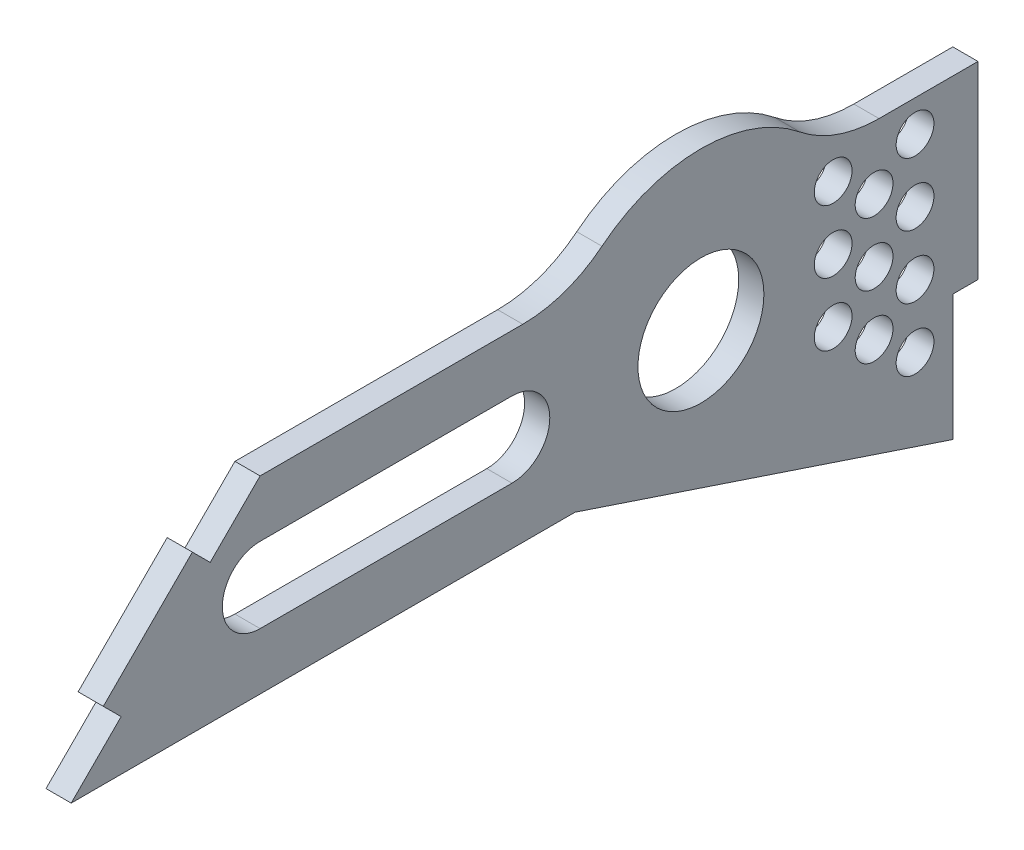
SolidWorks part; units mm, degrees
material "AISI 4340 Steel, normalized"
ref_plane "Front Plane" through (0, 0, 0) normal (0, 0, 1) x (1, 0, 0)
ref_plane "Top Plane" through (0, 0, 0) normal (0, 1, 0) x (1, 0, 0)
ref_plane "Right Plane" through (0, 0, 0) normal (1, 0, 0) x (0, 0, -1)
sketch "Sketch1" plane through (0, 0, 0) normal (1, 0, 0) x (0, 0, -1)
  line B0 (20, 0) -> (-20, 0)
  line B1 (-20, -12) -> (20, -12)
  line B2 (94, 49) -> (94, 24.7157)
  line B3 (21.7157, 9) -> (-20, 9)
  line B4 (-20, 9) -> (-50, -21)
  line B5 (-50, -21) -> (18.1966, -21)
  line B6 (40.5573, -26.2786) -> (90, -51)
  line B7 (90, -51) -> (90, 9)
  line B8 (90, 9) -> (94, 9)
  line B9 (94, 9) -> (94, -51)
  line B10 (94, -51) -> (119, 9)
  line B11 (119, 9) -> (119, 49)
  line B12 (119, 49) -> (94, 49)
  circle B13 centre (50, -6) radius 10
  arc B14 (20, -12) -> (20, 0) centre (20, -6) ccw
  arc B15 (78.2843, 9) -> (94, 24.7157) centre (78.2843, 24.7157) ccw
  arc B16 (65.7135, 13.4444) -> (78.2843, 9) centre (78.2843, 29) ccw
  arc B17 (65.7135, 13.4444) -> (34.2865, 13.4444) centre (50, -6) ccw
  arc B18 (21.7157, 9) -> (34.2865, 13.4444) centre (21.7157, 29) ccw
  arc B19 (40.5573, -26.2786) -> (18.1966, -21) centre (18.1966, -71) ccw
  arc B20 (-20, 0) -> (-20, -12) centre (-20, -6) ccw
  circle B21 centre (106.5, -6) radius 3
  circle B22 centre (106.5, 4) radius 3
  circle B23 centre (113, 9) radius 3
  circle B24 centre (106.5, 14) radius 3
  circle B25 centre (113, 19) radius 3
  circle B26 centre (106.5, 24) radius 3
  circle B27 centre (113, 29) radius 3
  circle B28 centre (113, 39) radius 3
  circle B29 centre (106.5, 34) radius 3
  circle B30 centre (100, 39) radius 3
  circle B31 centre (100, 29) radius 3
  circle B32 centre (100, 19) radius 3
  circle B33 centre (100, 9) radius 3
  circle B34 centre (100, -1) radius 3
  circle B35 centre (100, -11) radius 3
  circle B36 centre (100, -21) radius 3
  circle B37 centre (84, 4) radius 3
  circle B38 centre (84, -6) radius 3
  circle B39 centre (77.5, -1) radius 3
  circle B40 centre (71, 4) radius 3
  circle B41 centre (71, -6) radius 3
  circle B42 centre (77.5, -11) radius 3
  circle B43 centre (84, -16) radius 3
  circle B44 centre (71, -16) radius 3
  circle B45 centre (77.5, -21) radius 3
  circle B46 centre (84, -26) radius 3
  circle B47 centre (84, -36) radius 3
  circle B48 centre (77.5, -31) radius 3
  circle B49 centre (71, -26) radius 3
sketch_block_instance "Block-pedalbox side-1"
sketch_block "Block1"
sketch "Sketch2" plane through (0, 0, 0) normal (1, 0, 0) x (0, 0, -1)
  line L1 (119, 9) -> (119, 49) construction
  line L2 (94, 49) -> (94, 24.7157) construction
  line L3 (21.7157, 9) -> (-20, 9) construction
  line L4 (20, 0) -> (-20, 0) construction
  line L5 (-20, -12) -> (20, -12) construction
  line L6 (-50, -21) -> (18.1966, -21) construction
  line L7 (-20, 9) -> (-50, -21) construction
  line L9 (119, 9) -> (119, 44.9957)
  line L10 (94, 44.9957) -> (94, 24.7157)
  line L11 (21.7157, 9) -> (-20, 9)
  line L12 (20, 0) -> (-20, 0)
  line L13 (-20, -12) -> (20, -12)
  line L14 (-50, -21) -> (18.1966, -21)
  line L15 (-20, 9) -> (-27.9289, 1.0711)
  line L16 (94, 44.9957) -> (119, 44.9957)
  line L17 (90, -21) -> (94, -21)
  line L18 (90, -51) -> (90, 9) construction
  line L19 (94, 9) -> (94, -51) construction
  line L20 (90, 9) -> (94, 9) construction
  line L22 (30, -21) -> (90, -41)
  line L23 (18.1966, -21) -> (30, -21)
  line L24 (90, -41) -> (90, -21)
  line L25 (94, -21) -> (94, -41)
  line L26 (94, -41) -> (119, 9)
  line L27 (-35, -6) -> (-42.9011, 1.9011) construction
  line L28 (-27.9289, 1.0711) -> (-30.7574, 3.8995)
  line L29 (-30.7574, 3.8995) -> (-44.8995, -10.2426)
  line L30 (-44.8995, -10.2426) -> (-42.0711, -13.0711)
  line L31 (-42.0711, -13.0711) -> (-50, -21)
  line L32 (-42.0711, -13.0711) -> (-27.9289, 1.0711) construction
  arc A0 (78.2843, 9) -> (94, 24.7157) centre (78.2843, 24.7157) ccw construction
  arc A1 (65.7135, 13.4444) -> (78.2843, 9) centre (78.2843, 29) ccw construction
  arc A2 (65.7135, 13.4444) -> (34.2865, 13.4444) centre (50, -6) ccw construction
  arc A3 (21.7157, 9) -> (34.2865, 13.4444) centre (21.7157, 29) ccw construction
  arc A4 (20, -12) -> (20, 0) centre (20, -6) ccw construction
  arc A5 (-20, 0) -> (-20, -12) centre (-20, -6) ccw construction
  arc A6 (78.2843, 9) -> (94, 24.7157) centre (78.2843, 24.7157) ccw
  arc A7 (65.7135, 13.4444) -> (78.2843, 9) centre (78.2843, 29) ccw
  arc A8 (65.7135, 13.4444) -> (34.2865, 13.4444) centre (50, -6) ccw
  arc A9 (21.7157, 9) -> (34.2865, 13.4444) centre (21.7157, 29) ccw
  arc A10 (20, -12) -> (20, 0) centre (20, -6) ccw
  arc A11 (-20, 0) -> (-20, -12) centre (-20, -6) ccw
  circle A12 centre (50, -6) radius 10 construction
  circle A13 centre (50, -6) radius 10
  circle A14 centre (84, -26) radius 3 construction
  circle A15 centre (106.5, -6) radius 3 construction
  circle A16 centre (106.5, 4) radius 3 construction
  circle A17 centre (113, 9) radius 3 construction
  circle A18 centre (106.5, 14) radius 3 construction
  circle A19 centre (113, 19) radius 3 construction
  circle A20 centre (106.5, 24) radius 3 construction
  circle A21 centre (113, 29) radius 3 construction
  circle A22 centre (113, 39) radius 3 construction
  circle A23 centre (106.5, 34) radius 3 construction
  circle A24 centre (100, 39) radius 3 construction
  circle A25 centre (100, 29) radius 3 construction
  circle A26 centre (100, 19) radius 3 construction
  circle A27 centre (100, 9) radius 3 construction
  circle A28 centre (100, -1) radius 3 construction
  circle A29 centre (100, -11) radius 3 construction
  circle A30 centre (84, 4) radius 3 construction
  circle A31 centre (71, 4) radius 3 construction
  circle A32 centre (77.5, -1) radius 3 construction
  circle A33 centre (84, -6) radius 3 construction
  circle A34 centre (84, -16) radius 3 construction
  circle A35 centre (77.5, -11) radius 3 construction
  circle A36 centre (71, -6) radius 3 construction
  circle A37 centre (71, -16) radius 3 construction
  circle A38 centre (77.5, -21) radius 3 construction
  circle A39 centre (106.5, -6) radius 3
  circle A40 centre (106.5, 4) radius 3
  circle A41 centre (113, 9) radius 3
  circle A42 centre (106.5, 14) radius 3
  circle A43 centre (113, 19) radius 3
  circle A44 centre (106.5, 24) radius 3
  circle A45 centre (113, 29) radius 3
  circle A46 centre (113, 39) radius 3
  circle A47 centre (106.5, 34) radius 3
  circle A48 centre (100, 39) radius 3
  circle A49 centre (100, 29) radius 3
  circle A50 centre (100, 19) radius 3
  circle A51 centre (100, 9) radius 3
  circle A52 centre (100, -1) radius 3
  circle A53 centre (100, -11) radius 3
  circle A54 centre (84, 4) radius 3
  circle A55 centre (71, 4) radius 3
  circle A56 centre (77.5, -1) radius 3
  circle A57 centre (84, -6) radius 3
  circle A58 centre (84, -16) radius 3
  circle A59 centre (77.5, -11) radius 3
  circle A60 centre (71, -6) radius 3
  circle A61 centre (71, -16) radius 3
  circle A62 centre (84, -26) radius 3
  circle A63 centre (77.5, -21) radius 3
  dimension "D1" = 20.28
  dimension "D2" = 30
  dimension "D3" = 20
  dimension "D4" = 60
  dimension "D5" = 4
  dimension "D6" = 20
extrude "Boss-Extrude1" add sketch "Sketch2" along normal blind 4
sketch "Sketch3" plane through (0, 0, 0) normal (1, 0, 0) x (0, 0, -1)
  line L0 (94, -21) -> (94, 9)
  line L1 (94, 9) -> (78.2843, 9)
  line L2 (78.2843, 9) -> (78.2843, 52.4319)
  line L3 (78.2843, 52.4319) -> (131.1893, 52.4319)
  line L4 (131.1893, 52.4319) -> (131.1893, -47.3676)
  line L5 (131.1893, -47.3676) -> (90.8401, -47.3676)
  line L6 (90.8401, -47.3676) -> (94, -21)
extrude "Cut-Extrude3" cut sketch "Sketch3" against normal through all and the other way through all
